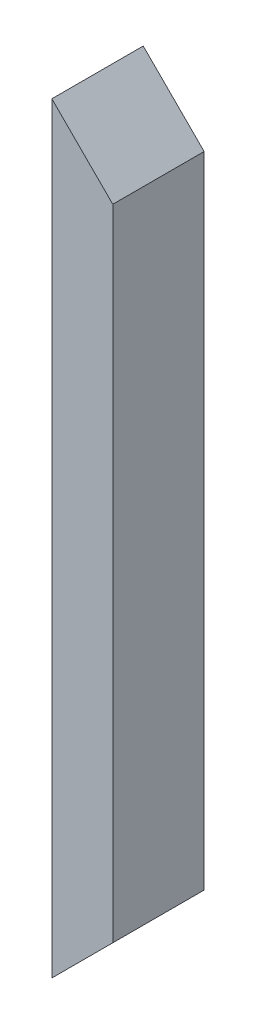
SolidWorks part; units mm, degrees
ref_plane "Plan de face" through (0, 0, 0) normal (0, 0, 1) x (1, 0, 0)
ref_plane "Plan de dessus" through (0, 0, 0) normal (0, 1, 0) x (1, 0, 0)
ref_plane "Plan de droite" through (0, 0, 0) normal (1, 0, 0) x (0, 0, -1)
sketch "Esquisse1" plane through (0, 0, 0) normal (0, 0, 1) x (1, 0, 0)
  line L0 (-350, -100) -> (-350, -350)
  line L1 (-350, -350) -> (-330, -330)
  line L2 (-330, -330) -> (-330, -120)
  line L3 (-330, -120) -> (-350, -100)
  point P4 (-314.9051, -306.1442)
  dimension "D1" = 45
  dimension "D2" = 45
  dimension "D3" = 20
  dimension "D4" = 250
extrude "Boss.-Extru.1" add sketch "Esquisse1" along normal blind 30
